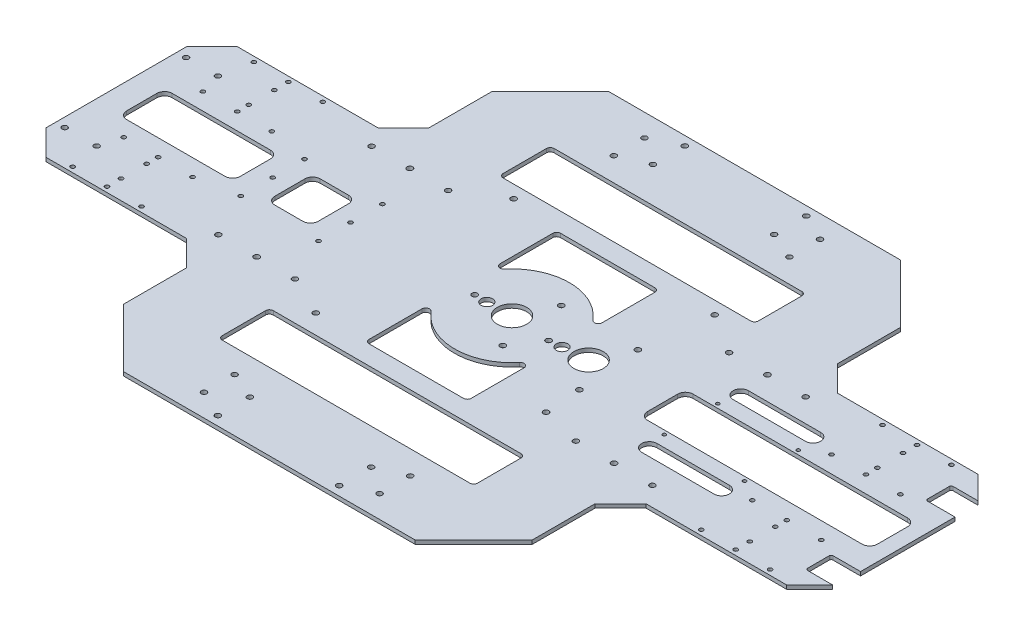
SolidWorks part; units mm, degrees
material "6061 合金"
ref_plane "前视基准面" through (0, 0, 0) normal (0, 0, 1) x (1, 0, 0)
ref_plane "上视基准面" through (0, 0, 0) normal (0, 1, 0) x (1, 0, 0)
ref_plane "右视基准面" through (0, 0, 0) normal (1, 0, 0) x (0, 0, -1)
sketch "草图1" plane through (0, 0, 0) normal (0, 1, 0) x (1, 0, 0)
  line L0 (-310, 75) -> (310, -75) construction
  line L1 (-260, 200) -> (260, 200) construction
  line L2 (-260, 200) -> (-260, -200) construction
  line L3 (-260, -200) -> (260, -200) construction
  line L4 (260, 200) -> (260, -200) construction
  line L5 (310, 75) -> (-310, -75) construction
  line L6 (-160, 200) -> (160, -200) construction
  line L7 (-310, -75) -> (-160, -75)
  line L8 (-310, -75) -> (-310, 75)
  line L9 (-310, 75) -> (-160, 75)
  line L10 (310, -75) -> (310, 75)
  line L11 (160, 200) -> (-160, -200) construction
  line L13 (-160, -200) -> (160, -200)
  line L14 (-160, -200) -> (-160, -75)
  line L15 (-160, 200) -> (160, 200)
  line L16 (160, -200) -> (160, -75)
  line L19 (-160, 75) -> (-160, 200)
  line L22 (160, 75) -> (310, 75)
  line L25 (160, 75) -> (160, 200)
  line L28 (160, -75) -> (310, -75)
  point P0 (0, 0)
  point P6 (-0.5159, 0.1248)
  point P11 (0, 0)
  dimension "D1" = 520
  dimension "D2" = 400
  dimension "D3" = 50
  dimension "D4" = 125
  dimension "D5" = 100
extrude "凸台-拉伸1" add sketch "草图1" along normal blind 3
chamfer "倒角1" distance 20 angle 45 8 edges at (-160, 1.5, -75) (-310, 1.5, -75) (-310, 1.5, 75) (-160, 1.5, 75) (160, 1.5, 75) (160, 1.5, -75) (310, 1.5, 75) (310, 1.5, -75)
sketch "草图2" plane through (0, 3, 0) normal (0, 1, 0) x (1, 0, 0)
  line L0 (-160, 200) -> (-160, 95) construction
  line L1 (-160, 180) -> (160, 180)
  line L2 (-160, 180) -> (-160, 200)
  line L3 (-160, 200) -> (160, 200)
  line L4 (160, 180) -> (160, 200)
  line L6 (160, -200) -> (-160, -200)
  line L7 (160, -200) -> (160, -180)
  line L8 (160, -180) -> (-160, -180)
  line L9 (-160, -200) -> (-160, -180)
  dimension "D1" = 20
  dimension "D2" = 20
extrude "切除-拉伸1" cut sketch "草图2" against normal blind 5
chamfer "倒角2" distance 50 angle 45 4 edges at (-160, 1.5, -180) (-160, 1.5, 180) (160, 1.5, -180) (160, 1.5, 180)
sketch "草图3" plane through (0, 3, 0) normal (0, 1, 0) x (1, 0, 0)
  line L0 (0, 0) -> (144.0598, 0) construction
  line L1 (110, -180) -> (-110, -180) construction
  circle A0 centre (-302.8263, 47.5) radius 2.1
  circle A1 centre (-277.8263, 47.5) radius 2.1
  circle A2 centre (-47.5, 182.8263) radius 2.1
  circle A3 centre (-47.5, 157.8263) radius 2.1
  circle A4 centre (47.5, 182.8263) radius 2.1
  circle A5 centre (47.5, 157.8263) radius 2.1
  circle A6 centre (302.7002, 47.5) radius 2.1
  circle A7 centre (327.7002, 47.5) radius 2.1
  circle A8 centre (-68.75, 172.5) radius 2.1
  circle A9 centre (-68.75, 148.5) radius 2.1
  circle A10 centre (68.75, 172.5) radius 2.1
  circle A11 centre (68.75, 148.5) radius 2.1
  circle A12 centre (68.75, -148.5) radius 2.1
  circle A13 centre (68.75, -172.5) radius 2.1
  circle A14 centre (-68.75, -148.5) radius 2.1
  circle A15 centre (-68.75, -172.5) radius 2.1
  circle A16 centre (327.7002, -47.5) radius 2.1
  circle A17 centre (302.7002, -47.5) radius 2.1
  circle A18 centre (47.5, -157.8263) radius 2.1
  circle A19 centre (47.5, -182.8263) radius 2.1
  circle A20 centre (-47.5, -157.8263) radius 2.1
  circle A21 centre (-47.5, -182.8263) radius 2.1
  circle A22 centre (-277.8263, -47.5) radius 2.1
  circle A23 centre (-302.8263, -47.5) radius 2.1
  dimension "D1" = 4.2
  dimension "D2" = 4.2
  dimension "D3" = 4.2
  dimension "D4" = 4.2
  dimension "D5" = 4.2
  dimension "D6" = 4.2
  dimension "D7" = 4.2
  dimension "D8" = 4.2
  dimension "D9" = 180
extrude "切除-拉伸2" cut sketch "草图3" against normal blind 80
sketch "草图4" plane through (0, 0, 0) normal (0, -1, 0) x (1, 0, 0)
  circle A0 centre (-78.74, 74.91) radius 2.15
  circle A2 centre (-78.74, -80.01) radius 2.15
  circle A3 centre (78.74, -80.01) radius 2.15
  circle A4 centre (78.74, 52.07) radius 2.15
  dimension "D1" = 4.3
  dimension "D2" = 4.3
  dimension "D3" = 4.3
  dimension "D4" = 4.3
extrude "切除-拉伸3" cut sketch "草图4" against normal blind 10
sketch "草图5" plane through (0, 3, 0) normal (0, 1, 0) x (1, 0, 0)
  line L0 (0, 0) -> (90.3311, 0) construction
  line L1 (0, 0) -> (0, 46.0052) construction
  circle A0 centre (219.2002, 71) radius 1.6
  circle A1 centre (273.2002, 71) radius 1.6
  circle A2 centre (246.2002, 71) radius 1.6
  circle A3 centre (219.2002, 30.9984) radius 1.6
  circle A4 centre (246.2002, 30.9984) radius 1.6
  circle A5 centre (273.2002, 30.9984) radius 1.6
  circle A6 centre (246.2002, 60) radius 1.6
  circle A7 centre (246.2002, 40) radius 1.6
  circle A8 centre (246.2002, -40) radius 1.6
  circle A9 centre (246.2002, -60) radius 1.6
  circle A10 centre (273.2002, -30.9984) radius 1.6
  circle A11 centre (246.2002, -30.9984) radius 1.6
  circle A12 centre (219.2002, -30.9984) radius 1.6
  circle A13 centre (246.2002, -71) radius 1.6
  circle A14 centre (273.2002, -71) radius 1.6
  circle A15 centre (219.2002, -71) radius 1.6
  circle A16 centre (-219.2002, -71) radius 1.6
  circle A17 centre (-273.2002, -71) radius 1.6
  circle A18 centre (-246.2002, -71) radius 1.6
  circle A19 centre (-219.2002, -30.9984) radius 1.6
  circle A20 centre (-246.2002, -30.9984) radius 1.6
  circle A21 centre (-273.2002, -30.9984) radius 1.6
  circle A22 centre (-246.2002, -60) radius 1.6
  circle A23 centre (-246.2002, -40) radius 1.6
  circle A24 centre (-246.2002, 40) radius 1.6
  circle A25 centre (-246.2002, 60) radius 1.6
  circle A26 centre (-273.2002, 30.9984) radius 1.6
  circle A27 centre (-246.2002, 30.9984) radius 1.6
  circle A28 centre (-219.2002, 30.9984) radius 1.6
  circle A29 centre (-246.2002, 71) radius 1.6
  circle A30 centre (-273.2002, 71) radius 1.6
  circle A31 centre (-219.2002, 71) radius 1.6
  circle A32 centre (170, -60) radius 2.1
  circle A34 centre (110, -60) radius 2.1
  circle A35 centre (140, -60) radius 2.2
  circle A36 centre (140, 60) radius 2.2
  circle A37 centre (110, 60) radius 2.1
  circle A38 centre (170, 60) radius 2.1
  circle A39 centre (-170, 60) radius 2.1
  circle A40 centre (-110, 60) radius 2.1
  circle A41 centre (-140, 60) radius 2.2
  circle A42 centre (-140, -60) radius 2.2
  circle A43 centre (-110, -60) radius 2.1
  circle A44 centre (-170, -60) radius 2.1
  dimension "D1" = 3.2
extrude "切除-拉伸4" cut sketch "草图5" against normal blind 29
sketch "草图6" plane through (0, 3, 0) normal (0, 1, 0) x (1, 0, 0)
  line L0 (160, -150) -> (160, -95) construction
  line L1 (0, 0) -> (166.252, 0) construction
  line L2 (-160, 130) -> (-110, 180)
  line L3 (110, 180) -> (-110, 180)
  line L4 (110, 180) -> (160, 130)
  line L5 (-160, -95) -> (-160, -150) construction
  line L12 (160, -144.1421) -> (160, -130)
  line L13 (114.1421, -190) -> (160, -144.1421)
  line L14 (52.4797, -190) -> (114.1421, -190)
  line L15 (-114.1421, -190) -> (-52, -190)
  line L16 (-160, -144.1421) -> (-114.1421, -190)
  line L17 (-160, -130) -> (-160, -144.1421)
  line L25 (-52, -190) -> (52.4797, -190)
  line L28 (110, -180) -> (160, -130) construction
  line L29 (110, -180) -> (-110, -180) construction
  line L30 (-160, -130) -> (-110, -180) construction
  line L31 (110, -180) -> (160, -130)
  line L32 (110, -180) -> (-110, -180)
  line L33 (-160, -130) -> (-110, -180)
  line L37 (-52, 190) -> (52.4797, 190)
  line L38 (-160, 130) -> (-160, 144.1421)
  line L39 (-160, 144.1421) -> (-114.1421, 190)
  line L40 (-114.1421, 190) -> (-52, 190)
  line L41 (52.4797, 190) -> (114.1421, 190)
  line L42 (114.1421, 190) -> (160, 144.1421)
  line L43 (160, 144.1421) -> (160, 130)
  dimension "D1" = 10
  dimension "D2" = 10
  dimension "D3" = 10
extrude "凸台-拉伸2" add sketch "草图6" against normal blind 3
sketch "草图7" plane through (0, 3, 0) normal (0, 1, 0) x (1, 0, 0)
  line L0 (310, -55) -> (310, 55) construction
  line L1 (310, 37) -> (287, 37)
  line L2 (310, 37) -> (310, 57)
  line L3 (310, 57) -> (287, 57)
  line L4 (287, 37) -> (287, 57)
  line L5 (290, 75) -> (180, 75) construction
  line L6 (310, -37) -> (287, -37)
  line L7 (310, -37) -> (310, -57)
  line L8 (310, -57) -> (287, -57)
  line L9 (287, -37) -> (287, -57)
  line L10 (180, -75) -> (290, -75) construction
  dimension "D1" = 18
  dimension "D2" = 20
  dimension "D3" = 20
  dimension "D4" = 18
  dimension "D5" = 23
extrude "切除-拉伸5" cut sketch "草图7" against normal blind 3
fillet "圆角1" radius 1.5 4 edges at (287, 1.5, 37) (287, 1.5, 57) (287, 1.5, -37) (287, 1.5, -57)
sketch "草图9" plane through (0, 0, 0) normal (0, -1, 0) x (1, 0, 0)
  line L0 (-45.449, 182.8784) -> (-49.551, 182.8784) construction
  line L1 (49.551, 182.8784) -> (45.449, 182.8784) construction
  line L2 (0, 0) -> (154.6544, 0) construction
  circle A0 centre (-47.5, 182.8784) radius 2.15
  circle A1 centre (47.5, 182.8784) radius 2.15
  circle A2 centre (47.5, -182.8784) radius 2.15
  circle A3 centre (-47.5, -182.8784) radius 2.15
  dimension "D1" = 4.3
extrude "切除-拉伸6" cut sketch "草图9" against normal blind 3
sketch "草图10" plane through (0, 0, 0) normal (0, -1, 0) x (1, 0, 0)
  circle A0 centre (60, 0) radius 11.5
  circle A1 centre (40.8185, 1.6223) radius 4.5
  circle A2 centre (72.3318, -26.2474) radius 2.15
  circle A3 centre (76.565, 23.8034) radius 2.15
  circle A4 centre (31.1032, 2.4441) radius 2.15
  dimension "D1" = 4.3
  dimension "D2" = 23
  dimension "D3" = 9
extrude "切除-拉伸7" cut sketch "草图10" against normal blind 5
sketch "草图11" plane through (0, 0, 0) normal (0, -1, 0) x (1, 0, 0)
  line L0 (-290, 75) -> (-180, 75) construction
  line L2 (-187.4745, 25) -> (-126.5, 25) construction
  line L3 (-187.4745, 25) -> (-187.4745, -25) construction
  line L4 (-187.4745, -25) -> (-126.5, -25) construction
  line L5 (-126.5, 25) -> (-126.5, -25) construction
  line L6 (-187.4745, 25) -> (-126.5, 25) construction
  line L7 (-187.4745, 25) -> (-187.4745, 0) construction
  line L8 (-187.4745, 0) -> (-126.5, 0) construction
  line L9 (-126.5, 25) -> (-126.5, 0) construction
  circle A6 centre (-126.5, -25) radius 1.6
  circle A7 centre (-187.5, -25) radius 1.6
  circle A8 centre (-126.5, 0) radius 1.6
  circle A9 centre (-187.4745, 0) radius 1.6
  circle A10 centre (-187.4745, 25) radius 1.6
  circle A11 centre (-126.5, 25) radius 1.6
  dimension "D1" = 50
  dimension "D2" = 25
  dimension "D3" = 60.9745
extrude "切除-拉伸8" cut sketch "草图11" against normal blind 10
sketch "草图12" plane through (0, 0, 0) normal (0, -1, 0) x (1, 0, 0)
  circle A0 centre (60, 0) radius 140
  dimension "D1" = 280
sketch "草图13" plane through (0, 3, 0) normal (0, 1, 0) x (1, 0, 0)
  line L0 (143.4002, 35.8) -> (200.0002, 35.8) construction
  line L1 (143.4002, 41.8) -> (200.0002, 41.8)
  line L2 (143.4002, 29.8) -> (200.0002, 29.8)
  line L3 (143.4002, -35.8) -> (200.0002, -35.8) construction
  line L4 (143.4002, -29.8) -> (200.0002, -29.8)
  line L5 (143.4002, -41.8) -> (200.0002, -41.8)
  line L6 (137.4002, 15.5) -> (137.4002, 21) construction
  line L7 (206.0002, -21) -> (206.0002, 21) construction
  line L8 (137.4002, -21) -> (137.4002, -15.5) construction
  line L9 (140.2002, 23.8) -> (203.2002, 23.8) construction
  line L10 (140.2002, -23.8) -> (203.2002, -23.8) construction
  circle A0 centre (140.2002, 21) radius 1.35
  circle A1 centre (203.2002, 21) radius 1.35
  circle A2 centre (203.2002, -21) radius 1.35
  circle A3 centre (140.2002, -21) radius 1.35
  arc A4 (143.4002, 41.8) -> (143.4002, 29.8) centre (143.4002, 35.8) ccw
  arc A5 (200.0002, 29.8) -> (200.0002, 41.8) centre (200.0002, 35.8) ccw
  arc A6 (143.4002, -29.8) -> (143.4002, -41.8) centre (143.4002, -35.8) ccw
  arc A7 (200.0002, -41.8) -> (200.0002, -29.8) centre (200.0002, -35.8) ccw
  point P14 (171.7002, 35.8)
  point P19 (171.7002, -35.8)
  dimension "D3" = 6
  dimension "D6" = 6
  dimension "D1" = 6
  dimension "D2" = 6
  dimension "D4" = 6
  dimension "D5" = 6
  dimension "D7" = 6
  dimension "D8" = 6
extrude "切除-拉伸9" cut sketch "草图13" against normal blind 3
sketch "草图14" plane through (0, 3, 0) normal (0, 1, 0) x (1, 0, 0)
  line L0 (143.4002, 29.8) -> (200.0002, 29.8) construction
  line L1 (292, 17.8) -> (124, 17.8)
  line L2 (298, 11.8) -> (298, -11.8)
  line L3 (292, -17.8) -> (124, -17.8)
  line L4 (118, 11.8) -> (118, -11.8)
  line L5 (200.0002, -29.8) -> (143.4002, -29.8) construction
  line L6 (310, -37) -> (310, 37) construction
  arc A0 (292, 17.8) -> (298, 11.8) centre (292, 11.8) cw
  arc A1 (298, -11.8) -> (292, -17.8) centre (292, -11.8) cw
  arc A2 (124, -17.8) -> (118, -11.8) centre (124, -11.8) cw
  arc A3 (124, 17.8) -> (118, 11.8) centre (124, 11.8) ccw
  point P12 (298, 17.8)
  point P19 (118, 17.8)
  dimension "D5" = 6
  dimension "D1" = 12
  dimension "D2" = 12
  dimension "D3" = 12
  dimension "D4" = 180
extrude "切除-拉伸10" cut sketch "草图14" against normal blind 3
sketch "草图15" plane through (0, 3, 0) normal (0, 1, 0) x (1, 0, 0)
  line L0 (60, 0) -> (-109.9354, 0) construction
  line L1 (72.3318, 26.2474) -> (-47.4576, 26.2474) construction
  line L2 (76.565, -23.8034) -> (-55.7658, -23.8034) construction
  line L3 (40.8185, -1.6223) -> (-96.5262, 0.8923) construction
  circle A0 centre (76.565, -23.8034) radius 2.15 construction
  circle A1 centre (72.3318, 26.2474) radius 2.15 construction
  circle A2 centre (31.1032, -2.4441) radius 2.15 construction
  circle A3 centre (40.8185, -1.6223) radius 4.5 construction
  circle A4 centre (60, 0) radius 11.5 construction
  circle A5 centre (76.565, -23.8034) radius 2.15
  circle A6 centre (72.3318, 26.2474) radius 2.15
  circle A7 centre (31.1032, -2.4441) radius 2.15
  circle A8 centre (40.8185, -1.6223) radius 4.5
  circle A9 centre (60, 0) radius 11.5
  circle A10 centre (16.565, -23.8034) radius 2.15
  circle A11 centre (12.3318, 26.2474) radius 2.15
  circle A12 centre (-28.8968, -0.3459) radius 2.15
  circle A13 centre (-19.1815, -0.5238) radius 4.5
  circle A14 centre (0, 0) radius 11.5
  dimension "D1" = 60
  dimension "D2" = 60
  dimension "D3" = 60
  dimension "D4" = 60
  dimension "D5" = 60
extrude "切除-拉伸11" cut sketch "草图15" against normal blind 3
sketch "草图16" plane through (0, 3, 0) normal (0, 1, 0) x (1, 0, 0)
  line L2 (-114.1421, 190) -> (114.1421, 190) construction
  line L7 (-97, 130) -> (97, 130)
  line L8 (-100, 127) -> (-100, 93)
  line L44 (-97, 90) -> (-40, 90)
  line L45 (-40, -90) -> (40, -90)
  line L53 (100, 127) -> (100, 93)
  line L70 (-40, 130) -> (40, 130)
  line L71 (-40, 72) -> (-40, 30.5778)
  line L72 (-40, -130) -> (40, -130)
  line L73 (40, 72) -> (40, 30.5778)
  line L74 (-97, -90) -> (-40, -90)
  line L75 (-100, -93) -> (-100, -127)
  line L76 (-97, -130) -> (97, -130)
  line L77 (100, -93) -> (100, -127)
  line L78 (-114.1421, -190) -> (114.1421, -190) construction
  line L79 (160, 95) -> (160, 144.1421) construction
  line L80 (-160, 144.1421) -> (-160, 95) construction
  line L81 (40, 90) -> (97, 90)
  line L82 (-40, -30.5778) -> (-40, -72)
  line L83 (40, -30.5778) -> (40, -72)
  line L84 (40, -90) -> (97, -90)
  line L85 (-37, -75) -> (37, -75)
  line L87 (-40, 90) -> (40, 90)
  line L89 (-37, 75) -> (37, 75)
  arc A56 (-34.6875, -28.6667) -> (34.6875, -28.6667) centre (0, 0) ccw
  arc A57 (34.6875, 28.6667) -> (-34.6875, 28.6667) centre (0, 0) ccw
  arc A58 (-40, -72) -> (-37, -75) centre (-37, -72) ccw
  arc A59 (37, -75) -> (40, -72) centre (37, -72) ccw
  arc A60 (97, -130) -> (100, -127) centre (97, -127) ccw
  arc A61 (97, -90) -> (100, -93) centre (97, -93) cw
  arc A62 (-100, -127) -> (-97, -130) centre (-97, -127) ccw
  arc A63 (-97, -90) -> (-100, -93) centre (-97, -93) ccw
  arc A64 (-100, 93) -> (-97, 90) centre (-97, 93) ccw
  arc A65 (-97, 130) -> (-100, 127) centre (-97, 127) ccw
  arc A66 (97, 130) -> (100, 127) centre (97, 127) cw
  arc A67 (97, 90) -> (100, 93) centre (97, 93) ccw
  arc A68 (37, 75) -> (40, 72) centre (37, 72) cw
  arc A69 (-40, 72) -> (-37, 75) centre (-37, 72) cw
  arc A70 (-34.6875, -28.6667) -> (-40, -30.5778) centre (-37, -30.5778) ccw
  arc A71 (40, -30.5778) -> (34.6875, -28.6667) centre (37, -30.5778) ccw
  arc A72 (40, 30.5778) -> (34.6875, 28.6667) centre (37, 30.5778) cw
  arc A73 (-34.6875, 28.6667) -> (-40, 30.5778) centre (-37, 30.5778) cw
  point P39 (100, -130)
  point P42 (100, -90)
  point P53 (100, 130)
  point P56 (100, 90)
  point P63 (-40, -20.6155)
  point P68 (40, 20.6155)
  dimension "D5" = 60
  dimension "D11" = 90
  dimension "D14" = 3
  dimension "D1" = 60
  dimension "D2" = 60
  dimension "D3" = 60
  dimension "D4" = 60
  dimension "D6" = 60
  dimension "D7" = 60
  dimension "D8" = 60
  dimension "D9" = 40
  dimension "D10" = 40
  dimension "D12" = 15
  dimension "D13" = 15
extrude "切除-拉伸12" cut sketch "草图16" against normal blind 3 contours L81 A67 L53 A66 L7 A65 L8 A64 L44 L87 | A73 A57 A72 L73 A68 L89 A69 L71 | L83 A71 A56 A70 L82 A58 L85 A59 | L74 A63 L75 A62 L76 L72 A60 L77 A61 L84 L45
sketch "草图17" plane through (0, 3, 0) normal (0, 1, 0) x (1, 0, 0)
  line L1 (-283.954, 17.8) -> (-207, 17.8)
  line L2 (-289.954, 11.8) -> (-289.954, -11.8)
  line L3 (-283.954, -17.8) -> (-207, -17.8)
  line L4 (-201, 11.8) -> (-201, -11.8)
  line L5 (-168, 17.8) -> (-146, 17.8)
  line L6 (-174, 11.8) -> (-174, -11.8)
  line L7 (-168, -17.8) -> (-146, -17.8)
  line L8 (-140, 11.8) -> (-140, -11.8)
  line L14 (-301.954, 33.3431) -> (-301.954, -33.3431) construction
  arc A4 (-146, 17.8) -> (-140, 11.8) centre (-146, 11.8) cw
  arc A5 (-146, -17.8) -> (-140, -11.8) centre (-146, -11.8) ccw
  arc A6 (-174, -11.8) -> (-168, -17.8) centre (-168, -11.8) ccw
  arc A7 (-168, 17.8) -> (-174, 11.8) centre (-168, 11.8) ccw
  arc A8 (-207, 17.8) -> (-201, 11.8) centre (-207, 11.8) cw
  arc A9 (-207, -17.8) -> (-201, -11.8) centre (-207, -11.8) ccw
  arc A10 (-289.954, -11.8) -> (-283.954, -17.8) centre (-283.954, -11.8) ccw
  arc A11 (-283.954, 17.8) -> (-289.954, 11.8) centre (-283.954, 11.8) ccw
  dimension "D1" = 12
extrude "切除-拉伸13" cut sketch "草图17" against normal blind 3
